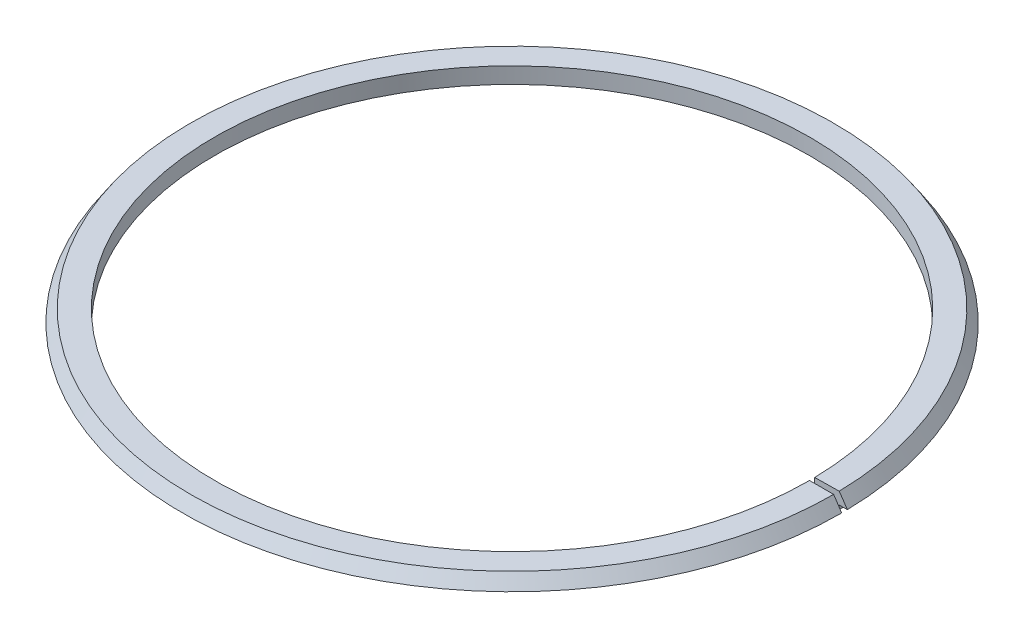
SolidWorks part; units mm, degrees
ref_plane "前视基准面" through (0, 0, 0) normal (0, 0, 1) x (1, 0, 0)
ref_plane "上视基准面" through (0, 0, 0) normal (0, 1, 0) x (1, 0, 0)
ref_plane "右视基准面" through (0, 0, 0) normal (1, 0, 0) x (0, 0, -1)
sketch "草图1" plane through (0, 0, 0) normal (0, 0, 1) x (1, 0, 0)
  line L0 (0, 9.1462) -> (0, -5.4877) construction
  line L1 (37, 2) -> (37, 0)
  line L2 (40, 0.5) -> (41, 0.5)
  line L3 (40, 0.5) -> (40, 0)
  line L5 (37, 0) -> (40, 0)
  line L6 (37, 2) -> (40, 2)
  line L7 (40, 2) -> (41, 0.5)
  dimension "D1" = 37
  dimension "D2" = 3
  dimension "D3" = 1
  dimension "D4" = 0.5
  dimension "D5" = 2
  dimension "D6" = 3
revolve "旋转1" add sketch "草图1" angle 359 about L0
